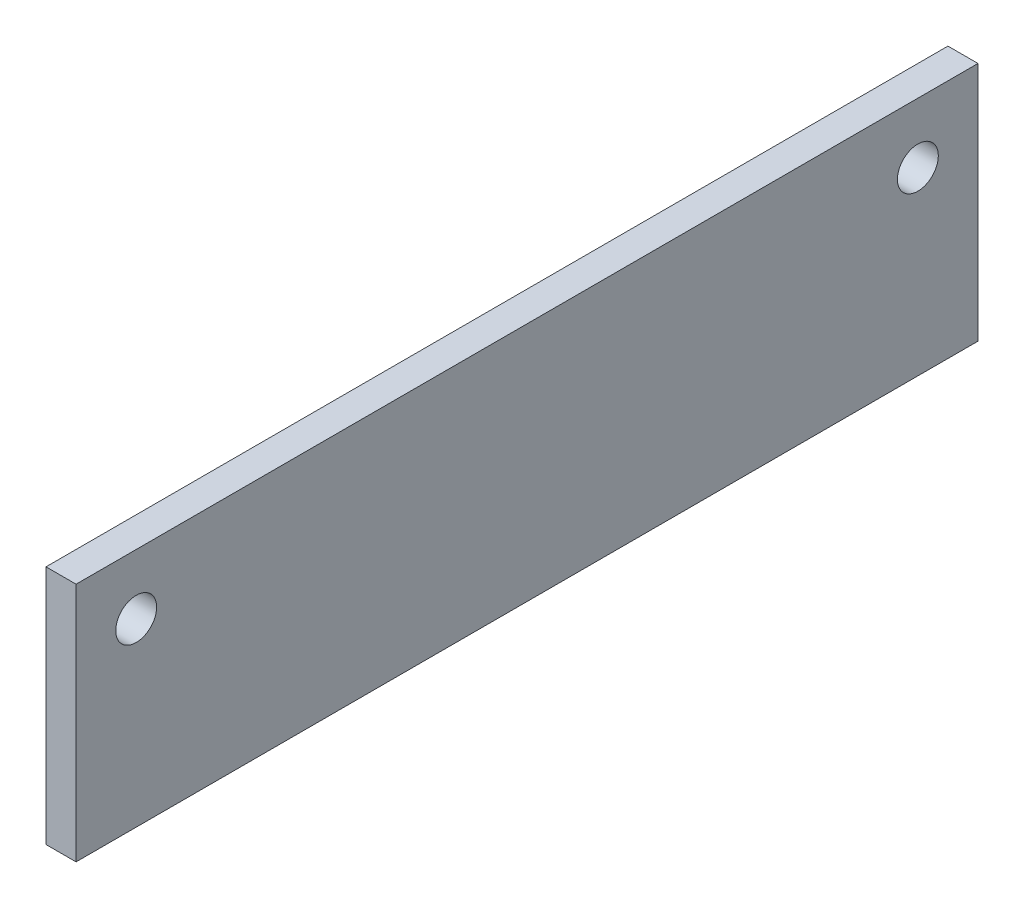
SolidWorks part; units mm, degrees
ref_plane "Front" through (0, 0, 0) normal (0, 0, 1) x (1, 0, 0)
ref_plane "Top" through (0, 0, 0) normal (0, 1, 0) x (1, 0, 0)
ref_plane "Right" through (0, 0, 0) normal (1, 0, 0) x (0, 0, -1)
sketch "Sketch1" plane through (0, 0, 0) normal (1, 0, 0) x (0, 0, -1)
  line L0 (37.5, 0) -> (-37.5, 0)
  line L1 (-37.5, 10) -> (37.5, 10)
  line L2 (-37.5, 10) -> (-37.5, -10)
  line L3 (-37.5, -10) -> (37.5, -10)
  line L4 (37.5, 10) -> (37.5, -10)
  line L5 (-37.5, 10) -> (37.5, -10) construction
  line L6 (-37.5, -10) -> (37.5, 10) construction
  line L7 (-37.5, 0) -> (-37.5, 10)
  line L8 (-37.5, 5) -> (37.5, 5)
  circle A0 centre (32.5, 5) radius 1.7
  circle A1 centre (-32.5, 5) radius 1.7
  point P0 (0, 0)
  dimension "D3" = 5
  dimension "D1" = 75
  dimension "D2" = 20
  dimension "D4" = 5
extrude "Boss-Extrude1" add sketch "Sketch1" along normal blind 2.5 contours A1 L8 A0 L4 L1 L2 | A1 L8 L7 L0 L4 A0 | L4 L0 L2 L3
